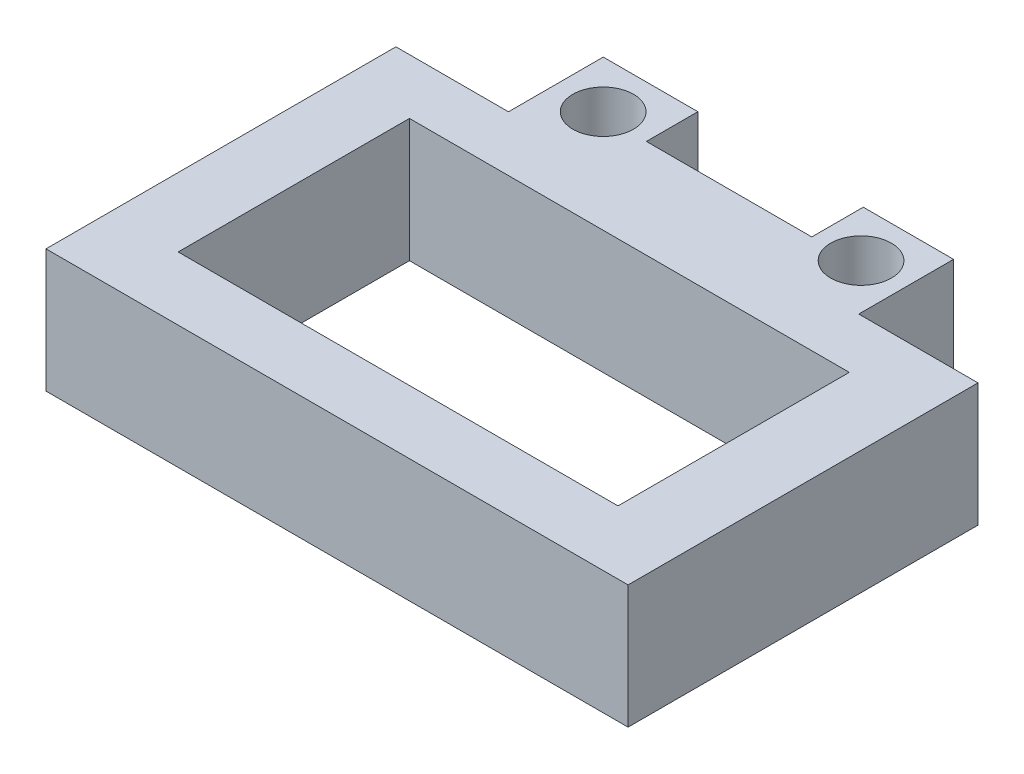
SolidWorks part; units mm, degrees
ref_plane "Front Plane" through (0, 0, 0) normal (0, 0, 1) x (1, 0, 0)
ref_plane "Top Plane" through (0, 0, 0) normal (0, 1, 0) x (1, 0, 0)
ref_plane "Right Plane" through (0, 0, 0) normal (1, 0, 0) x (0, 0, -1)
sketch "Sketch1" plane through (0, 0, 0) normal (0, 1, 0) x (1, 0, 0)
  line L0 (23.2084, 35.617) -> (23.2084, 32.9001)
  line L1 (15.9084, 27.7029) -> (39.1084, 27.7029)
  line L2 (15.9084, 27.7029) -> (15.9084, 15.5029)
  line L3 (15.9084, 15.5029) -> (39.1084, 15.5029)
  line L4 (39.1084, 27.7029) -> (39.1084, 15.5029)
  line L5 (12.281, 30.617) -> (42.9837, 30.617)
  line L6 (12.281, 30.617) -> (12.281, 12.1599)
  line L7 (12.281, 12.1599) -> (42.9837, 12.1599)
  line L8 (42.9837, 30.617) -> (42.9837, 12.1599)
  line L9 (31.8568, 35.617) -> (31.8949, 35.617)
  line L10 (18.2174, 35.617) -> (18.2174, 30.617)
  line L11 (18.2174, 30.617) -> (36.6953, 30.617)
  line L12 (36.6953, 35.617) -> (36.6953, 30.617)
  line L13 (23.2084, 32.9001) -> (31.933, 32.9001)
  line L14 (31.933, 32.9001) -> (31.933, 35.617)
  line L15 (18.2174, 35.617) -> (23.2084, 35.617)
  line L16 (31.933, 35.617) -> (36.6953, 35.617)
  circle A0 centre (20.7129, 33.117) radius 1.6
  circle A1 centre (34.3141, 33.117) radius 1.6
  point P30 (34.3141, 33.117)
  dimension "D4" = 3.2
  dimension "D5" = 3.2
  dimension "D1" = 23.2
  dimension "D2" = 12.2
  dimension "D3" = 5
extrude "Boss-Extrude5" add sketch "Sketch1" along normal blind 6.5 contours L8 L5 L6 L7 L1 L4 L3 L2 | L16 L14 L13 L0 L15 L10 L5 L12
